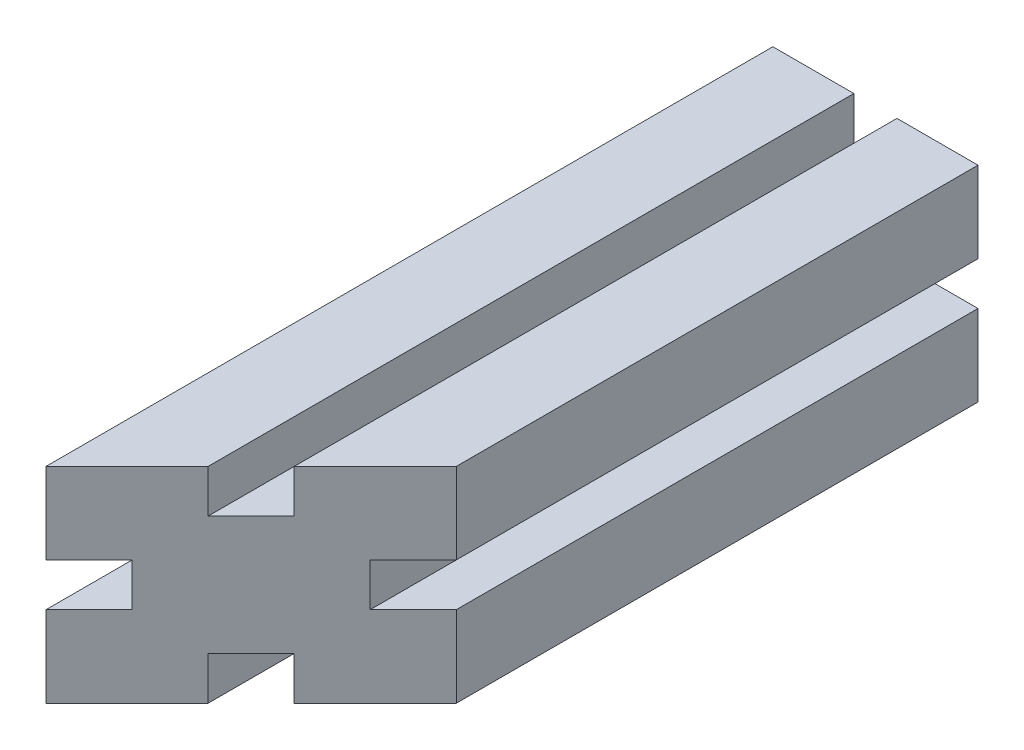
SolidWorks part; units mm, degrees
ref_plane "Front Plane" through (0, 0, 0) normal (0, 0, 1) x (1, 0, 0)
ref_plane "Top Plane" through (0, 0, 0) normal (0, 1, 0) x (1, 0, 0)
ref_plane "Right Plane" through (0, 0, 0) normal (1, 0, 0) x (0, 0, -1)
sketch "Sketch1" plane through (0, 0, 0) normal (0, 0, 1) x (1, 0, 0)
  line L0 (-19.05, -19.05) -> (-4, -19.05)
  line L1 (-4, -19.05) -> (-4, -11.05)
  line L2 (-4, -11.05) -> (4, -11.05)
  line L3 (4, -11.05) -> (4, -19.05)
  line L4 (4, -19.05) -> (19.05, -19.05)
  line L5 (19.05, -19.05) -> (19.05, -4)
  line L6 (19.05, -4) -> (11.05, -4)
  line L7 (11.05, -4) -> (11.05, 4)
  line L8 (11.05, 4) -> (19.05, 4)
  line L9 (19.05, 4) -> (19.05, 19.05)
  line L10 (19.05, 19.05) -> (4, 19.05)
  line L11 (4, 19.05) -> (4, 11.05)
  line L12 (4, 11.05) -> (-4, 11.05)
  line L13 (-4, 11.05) -> (-4, 19.05)
  line L14 (-4, 19.05) -> (-19.05, 19.05)
  line L15 (-19.05, 19.05) -> (-19.05, 4)
  line L16 (-19.05, 4) -> (-11.05, 4)
  line L17 (-11.05, 4) -> (-11.05, -4)
  line L18 (-11.05, -4) -> (-19.05, -4)
  line L19 (-19.05, -4) -> (-19.05, -19.05)
extrude "Profile" add sketch "Sketch1" along normal blind 135
sketch "Sketch2" plane through (0, 0, 0) normal (0, 1, 0) x (1, 0, 0)
  line L0 (-19.05, -135) -> (25, -90.95)
  line L1 (25, -90.95) -> (25, -145)
  line L2 (25, -145) -> (-19.05, -135)
extrude "Miter1" cut sketch "Sketch2" against normal through all and the other way through all
equation "\"length\" = 135.0mm"
equation "\"D1@Profile\" = \"length\""
